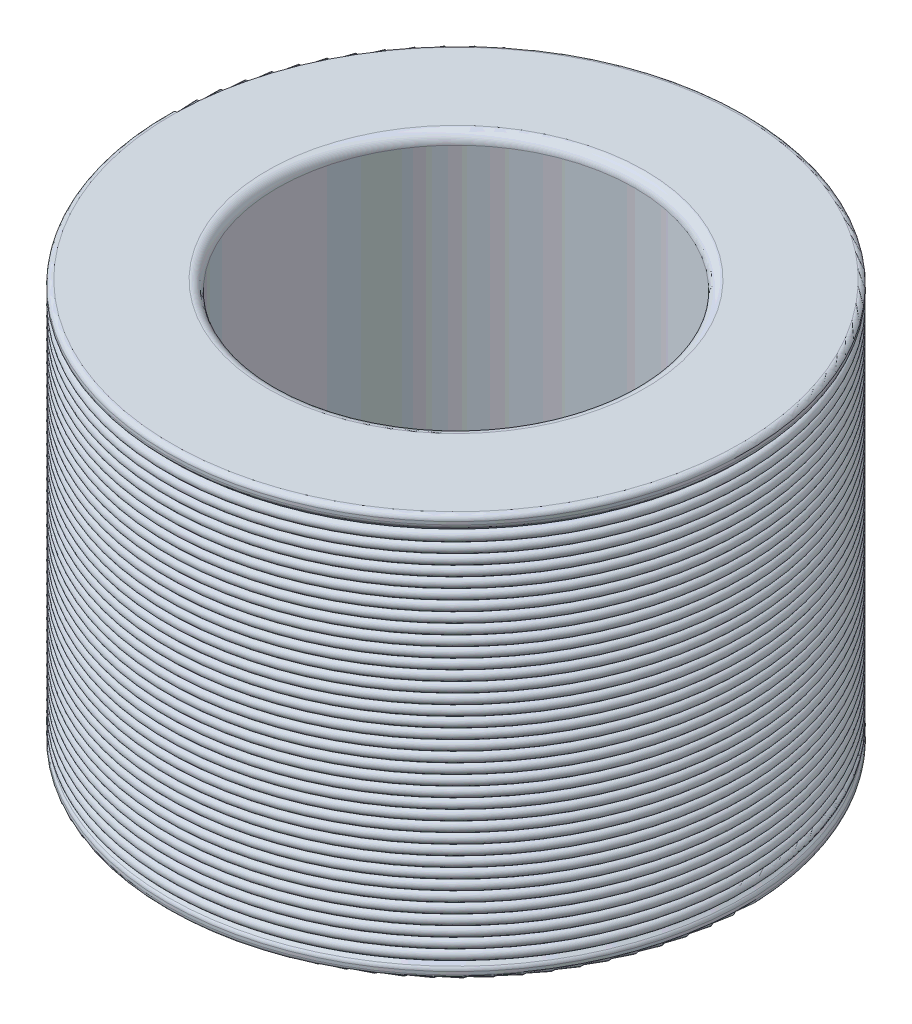
SolidWorks part; units mm, degrees
ref_plane "Front" through (0, 0, 0) normal (0, 0, 1) x (1, 0, 0)
ref_plane "Top" through (0, 0, 0) normal (0, 1, 0) x (1, 0, 0)
ref_plane "Right" through (0, 0, 0) normal (1, 0, 0) x (0, 0, -1)
sketch "Sketch1" plane through (0, 0, 0) normal (1, 0, 0) x (0, 0, -1)
  line L0 (0, 11.1343) -> (0, 0) construction
  line L1 (0, 0) -> (12.4358, 0) construction
  line L2 (3.55, 8) -> (5.75, 8)
  line L3 (5.75, 8) -> (5.75, 7.8)
  line L4 (5.75, 7.8) -> (5.65, 7.7)
  line L5 (5.5, 7.7) -> (5.5, 0.3)
  line L6 (5.65, 0.3) -> (5.75, 0.2)
  line L7 (5.75, 0.2) -> (5.75, 0)
  line L8 (5.75, 0) -> (3.55, 0)
  line L9 (3.55, 0) -> (3.55, 8)
  line L10 (5.65, 7.7) -> (5.5, 7.7)
  line L11 (3.55, 4) -> (5.9525, 4) construction
  line L12 (5.65, 0.3) -> (5.5, 0.3)
  dimension "D1" = 8
  dimension "D2" = 7.1
  dimension "D3" = 11.5
  dimension "D4" = 11
  dimension "D5" = 0.2
  dimension "D6" = 7.4
  dimension "D7" = 0.15
revolve "Revolve1" add sketch "Sketch1" angle 360 about L0
fillet "Fillet1" radius 0.2 2 edges at (0, 0, 3.55) (0, 8, 3.55)
fillet "Fillet2" radius 0.1 4 edges at (0, 0.2, 5.75) (0, 7.8, 5.75) (0, 8, 5.75) (0, 0, 5.75)
sketch "Sketch2" plane through (0, 0, 0) normal (1, 0, 0) x (0, 0, -1)
  line L0 (5.5, 7.7) -> (5.65, 7.7)
  line L1 (5.65, 7.5) -> (5.5, 7.5)
  line L2 (5.5, 7.5) -> (5.5, 7.7)
  line L7 (0, 0) -> (0, 10.0617) construction
  arc A0 (5.65, 7.7) -> (5.65, 7.5) centre (5.65, 7.6) cw
  dimension "D1" = 0.1
revolve "Revolve2" add sketch "Sketch2" angle 360 about L7
pattern_linear "LPattern1" count 37 spacing 0.2 along (0, -1, 0) of "Revolve2"
